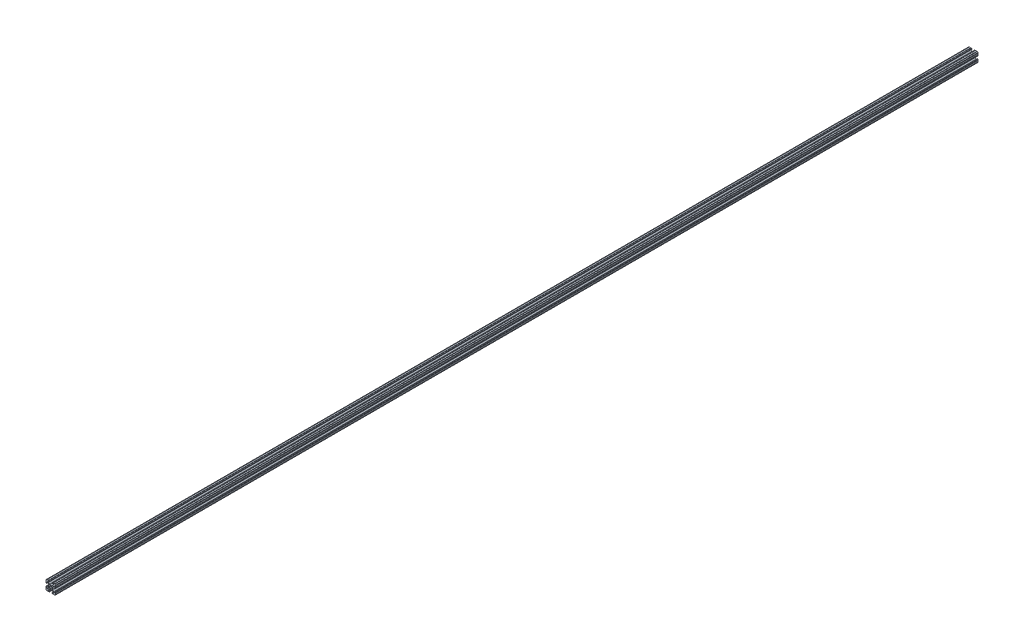
SolidWorks part; units mm, degrees
ref_plane "Front Plane" through (0, 0, 0) normal (0, 0, 1) x (1, 0, 0)
ref_plane "Top Plane" through (0, 0, 0) normal (0, 1, 0) x (1, 0, 0)
ref_plane "Right Plane" through (0, 0, 0) normal (1, 0, 0) x (0, 0, -1)
sketch "Sketch2" plane through (0, 0, 0) normal (0, 0, 1) x (1, 0, 0)
  line L0 (0, 12.7) -> (0, -12.7) construction
  line L1 (-12.7, 0) -> (12.7, 0) construction
  line L2 (3.2512, -12.7) -> (12.7, -12.7)
  line L3 (12.7, -12.7) -> (12.7, -3.2512)
  line L4 (3.2512, -12.7) -> (3.2512, -10.4902)
  line L5 (3.2512, -10.4902) -> (8.9276, -10.4902)
  line L6 (8.9276, -10.4902) -> (3.0856, -4.6482)
  line L7 (0, 0) -> (12.7, -12.7) construction
  line L8 (12.7, -3.2512) -> (10.4902, -3.2512)
  line L9 (10.4902, -3.2512) -> (10.4902, -8.9276)
  line L10 (10.4902, -8.9276) -> (4.6482, -3.0856)
  circle A0 centre (0, 0) radius 2.6035
  arc A1 (6.3485, -10.4902) -> (7.1039, -8.6665) centre (6.3485, -9.4219) ccw construction
  point P8 (0, -4.6482)
  dimension "Center Hole Diameter" = 5.207
  dimension "Rail Height" = 25.4
  dimension "Rail Width" = 25.4
  dimension "T-Slot Width" = 6.5024
  dimension "Slot Inner Width" = 14.8336
  dimension "Thickness" = 2.2098
  dimension "Slot Depth" = 5.842
  dimension "D1" = 2.2098
sketch "Sketch3" plane through (0, 0, 0) normal (1, 0, 0) x (0, 0, -1)
  line L0 (-1219.2, -12.7) -> (1219.2, -12.7) construction
  line L1 (-1193.8, 0) -> (1193.8, 0) construction
  dimension "Length" = 2438.4
  dimension "D1" = 25.4
sketch "Sketch4" plane through (0, 0, 0) normal (0, 0, 1) x (1, 0, 0)
  line L0 (4.1904, -12.7) -> (10.1173, -12.7)
  line L1 (3.2512, -12.7) -> (12.7, -12.7) construction
  line L2 (3.2512, -12.7) -> (3.2512, -10.4902) construction
  line L3 (3.2512, -10.4902) -> (8.9276, -10.4902) construction
  line L4 (3.2512, -11.4294) -> (3.2512, -11.7608)
  line L5 (4.1904, -10.4902) -> (6.3485, -10.4902)
  line L6 (0, -4.6482) -> (2.164, -4.6482)
  line L7 (8.9276, -10.4902) -> (3.0856, -4.6482) construction
  line L8 (3.7373, -5.2999) -> (7.1039, -8.6665)
  line L9 (12.7, -12.7) -> (12.7, -3.2512) construction
  line L10 (10.4902, -8.9276) -> (4.6482, -3.0856) construction
  line L11 (10.4902, -3.2512) -> (10.4902, -8.9276) construction
  line L12 (10.4902, -6.3485) -> (10.4902, -4.1904)
  line L13 (12.7, -3.2512) -> (10.4902, -3.2512) construction
  line L14 (11.4294, -3.2512) -> (11.7608, -3.2512)
  line L15 (12.7, -4.1904) -> (12.7, -10.1173)
  line L16 (8.6665, -7.1039) -> (5.2999, -3.7373)
  line L17 (4.6482, 0) -> (4.6482, -2.164)
  line L18 (-12.7, 0) -> (12.7, 0) construction
  line L19 (0, -4.6482) -> (0, -2.6035)
  line L20 (0, 12.7) -> (0, -12.7) construction
  line L21 (4.6482, 0) -> (2.6035, 0)
  arc A0 (3.2512, -11.7608) -> (4.1904, -12.7) centre (4.1904, -11.7608) ccw
  arc A2 (3.2512, -11.4294) -> (4.1904, -10.4902) centre (4.1904, -11.4294) cw
  arc A3 (6.3485, -10.4902) -> (7.1039, -8.6665) centre (6.3485, -9.4219) ccw
  arc A4 (2.164, -4.6482) -> (3.7373, -5.2999) centre (2.164, -6.8732) cw
  arc A5 (10.1173, -12.7) -> (12.7, -10.1173) centre (10.1173, -10.1173) ccw
  arc A6 (8.6665, -7.1039) -> (10.4902, -6.3485) centre (9.4219, -6.3485) ccw
  arc A7 (10.4902, -4.1904) -> (11.4294, -3.2512) centre (11.4294, -4.1904) cw
  arc A8 (11.7608, -3.2512) -> (12.7, -4.1904) centre (11.7608, -4.1904) cw
  arc A9 (5.2999, -3.7373) -> (4.6482, -2.164) centre (6.8732, -2.164) cw
  circle A10 centre (0, 0) radius 2.6035 construction
  arc A11 (0, -2.6035) -> (2.6035, 0) centre (0, 0) ccw
  dimension "D1" = 2.5827
  dimension "D2" = 2.225
  dimension "D3" = 0.9392
extrude "Boss-Extrude1" add sketch "Sketch4" along normal mid plane 2438.4
sketch "Sketch5" plane through (0, 0, 0) normal (0, 0, 1) x (1, 0, 0)
  line L0 (3.2512, -12.7) -> (12.7, -12.7) construction
  line L1 (4.1904, -10.4902) -> (6.3485, -10.4902) construction
  line L3 (0, 0) -> (12.7, -12.7) construction
  line L4 (6.3485, -10.4902) -> (6.3485, -12.7) construction
  line L5 (8.9276, -10.4902) -> (3.0856, -4.6482) construction
  circle A0 centre (10.3562, -12.7) radius 0.5524
  circle A1 centre (5.796, -12.7) radius 0.5524
  circle A2 centre (12.7, -10.3562) radius 0.5524
  circle A3 centre (12.7, -5.796) radius 0.5524
  point P10 (5.2694, -10.4902)
  point P12 (9.4219, -6.3485)
  dimension "D1" = 1.1049
extrude "Cut-Extrude1" cut sketch "Sketch5" against normal through all both and the other way through all
mirror "Mirror1" about plane through (0, 0, 0) normal (1, 0, 0) of bodies 137 134
mirror "Mirror2" about plane through (0, 0, 0) normal (0, 1, 0) of bodies 135
equation "\"D1@Boss-Extrude1\"=\"Length@Sketch3\""
equation "\"D1@Sketch2\"=\"Thickness@Sketch2\""
equation "\"D2@Sketch4\"=\"Slot Inner Width@Sketch2\"*0.15"
equation "\"D1@Sketch4\"=\"D3@Sketch4\"*2.75"
equation "\"D3@Sketch4\"=\"Thickness@Sketch2\"*0.425"
equation "\"D1@Sketch5\"=\"Thickness@Sketch2\"*0.5"
